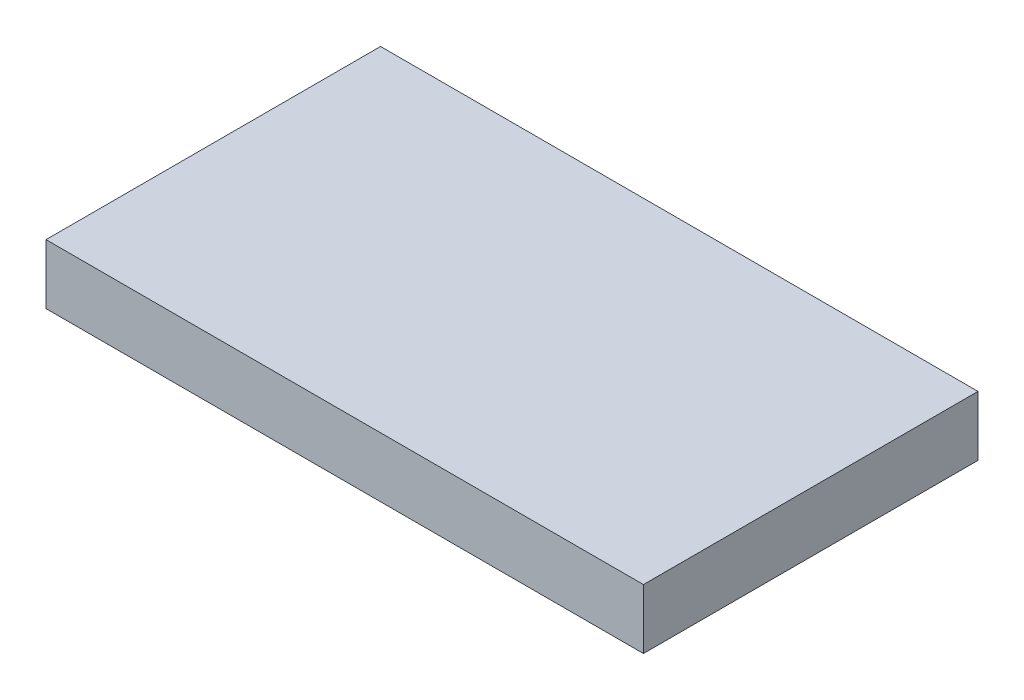
SolidWorks part; units mm, degrees
ref_plane "Front Plane" through (0, 0, 0) normal (0, 0, 1) x (1, 0, 0)
ref_plane "Top Plane" through (0, 0, 0) normal (0, 1, 0) x (1, 0, 0)
ref_plane "Right Plane" through (0, 0, 0) normal (1, 0, 0) x (0, 0, -1)
sketch "Sketch1" plane through (0, 0, 0) normal (0, 1, 0) x (1, 0, 0)
  line L1 (-63.5, -35.56) -> (63.5, -35.56)
  line L2 (-63.5, -35.56) -> (-63.5, 35.56)
  line L3 (-63.5, 35.56) -> (63.5, 35.56)
  line L4 (63.5, -35.56) -> (63.5, 35.56)
  line L5 (-63.5, -35.56) -> (63.5, 35.56) construction
  line L6 (-63.5, 35.56) -> (63.5, -35.56) construction
  point P0 (0, 0)
  dimension "D1" = 127
  dimension "D2" = 71.12
extrude "Boss-Extrude1" add sketch "Sketch1" along normal blind 12.7
